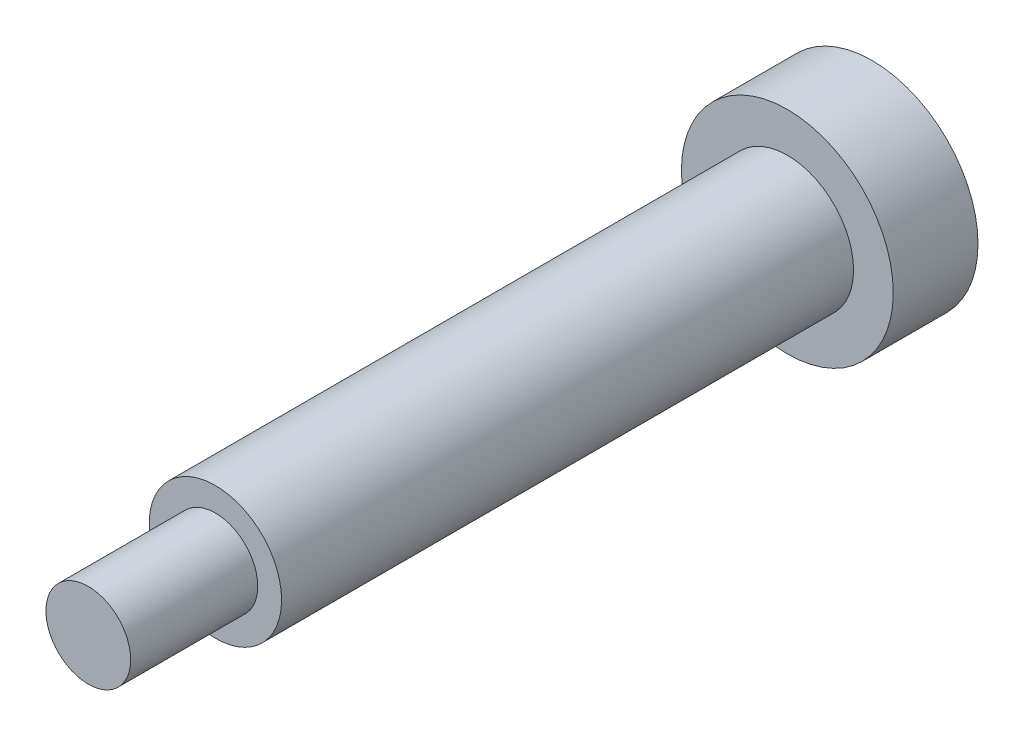
SolidWorks part; units mm, degrees
ref_plane "Front Plane" through (0, 0, 0) normal (0, 0, 1) x (1, 0, 0)
ref_plane "Top Plane" through (0, 0, 0) normal (0, 1, 0) x (1, 0, 0)
ref_plane "Right Plane" through (0, 0, 0) normal (1, 0, 0) x (0, 0, -1)
sketch "Sketch1" plane through (0, 0, 0) normal (0, 0, 1) x (1, 0, 0)
  circle A0 centre (0, 0) radius 5
extrude "Boss-Extrude1" add sketch "Sketch1" along normal blind 4
sketch "Sketch2" plane through (0, 0, 4) normal (0, 0, 1) x (1, 0, 0)
  circle A0 centre (0, 0) radius 3.125
  dimension "D1" = 6.25
extrude "Boss-Extrude2" add sketch "Sketch2" along normal blind 27
sketch "Sketch3" plane through (0, 0, 31) normal (0, 0, 1) x (1, 0, 0)
  circle A0 centre (0, 0) radius 2
extrude "Boss-Extrude3" add sketch "Sketch3" along normal blind 6
